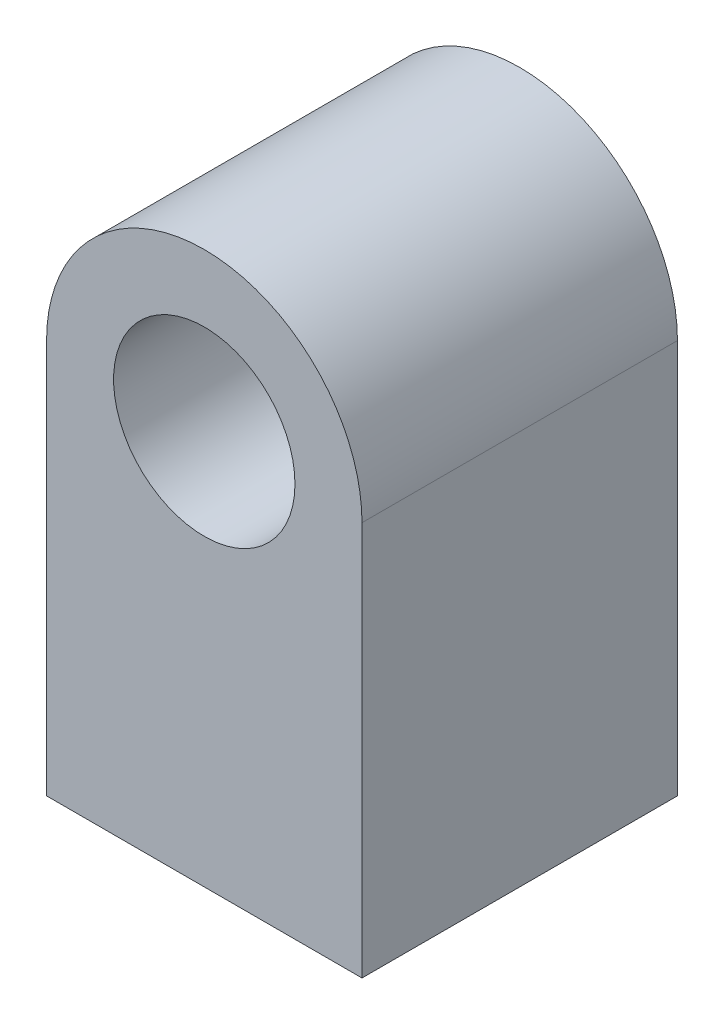
SolidWorks part; units mm, degrees
ref_plane "前视基准面" through (0, 0, 0) normal (0, 0, 1) x (1, 0, 0)
ref_plane "上视基准面" through (0, 0, 0) normal (0, 1, 0) x (1, 0, 0)
ref_plane "右视基准面" through (0, 0, 0) normal (1, 0, 0) x (0, 0, -1)
other "Configuration Table"
sketch "草图1" plane through (0, 0, 0) normal (0, 0, 1) x (1, 0, 0)
  line L0 (2, 0) -> (2, -5)
  line L1 (2, -5) -> (-2, -5)
  line L2 (-2, -5) -> (-2, 0)
  arc A0 (2, 0) -> (-2, 0) centre (0, 0) ccw
  circle A1 centre (0, 0) radius 1.15
  dimension "D1" = 2.3
  dimension "D2" = 2
  dimension "D3" = 5
extrude "凸台-拉伸1" add sketch "草图1" along normal blind 4
sketch "草图2" plane through (0, -5, 0) normal (0, -1, 0) x (1, 0, 0)
  line L0 (-2, 4) -> (-2, 0) construction
  circle A0 centre (0, 2) radius 1
  point P7 (-2, 2)
  dimension "D1" = 2
extrude "切除-拉伸1" cut sketch "草图2" against normal blind 3.5
